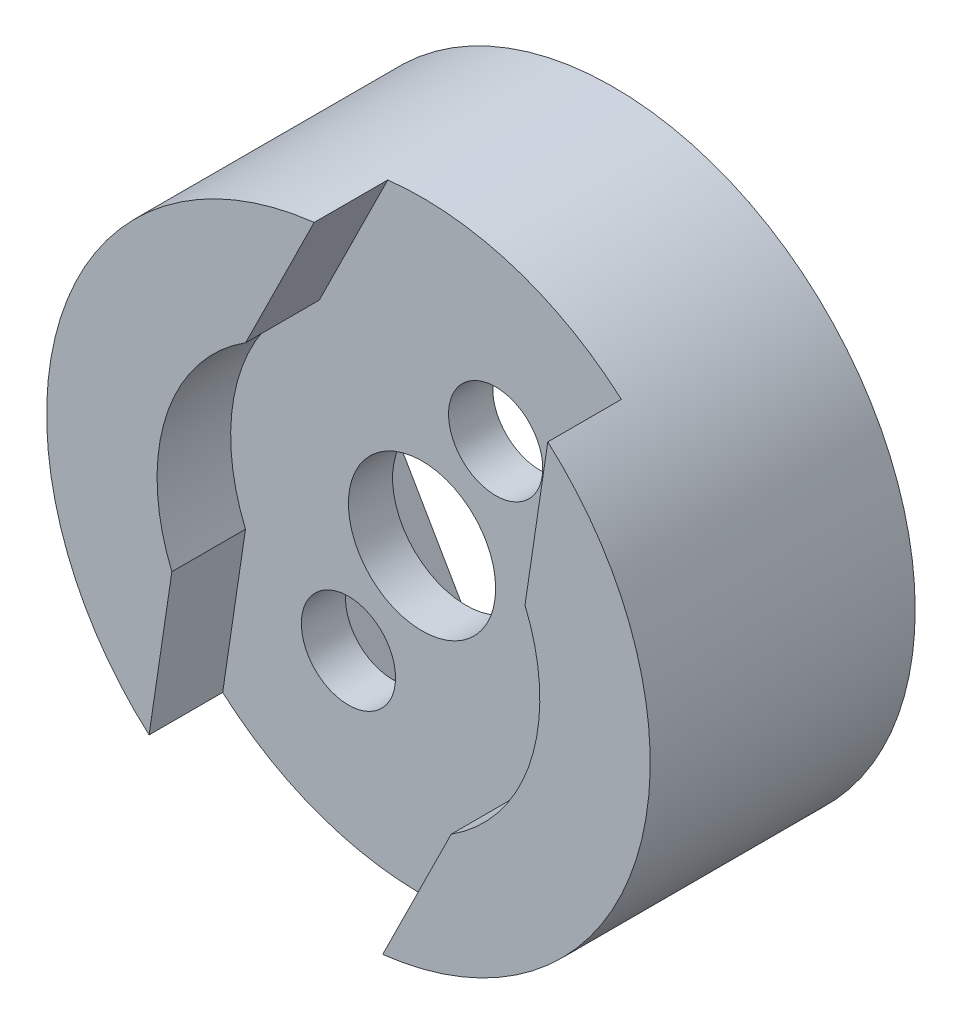
SolidWorks part; units mm, degrees
ref_plane "Front Plane" through (0, 0, 0) normal (0, 0, 1) x (1, 0, 0)
ref_plane "Top Plane" through (0, 0, 0) normal (0, 1, 0) x (1, 0, 0)
ref_plane "Right Plane" through (0, 0, 0) normal (1, 0, 0) x (0, 0, -1)
sketch "Sketch1" plane through (0, 0, 0) normal (0, 0, 1) x (1, 0, 0)
  line L1 (4.75, 8.2272) -> (-4.75, 8.2272)
  line L2 (-4.75, 8.2272) -> (-9.5, 0)
  line L3 (-9.5, 0) -> (-4.75, -8.2272)
  line L4 (-4.75, -8.2272) -> (4.75, -8.2272)
  line L5 (4.75, -8.2272) -> (9.5, 0)
  line L6 (9.5, 0) -> (4.75, 8.2272)
  circle A0 centre (0, 0) radius 10.25
  circle A1 centre (0, 0) radius 8.2272 construction
  dimension "D1" = 20.5
  dimension "D2" = 9.5
extrude "Boss-Extrude1" add sketch "Sketch1" along normal blind 5
sketch "Sketch2" plane through (0, 0, 5) normal (0, 0, 1) x (1, 0, 0)
  circle A1 centre (0, 0) radius 10.25
  circle A2 centre (0, 0) radius 10.25
  dimension "D1" = 0
extrude "Boss-Extrude2" add sketch "Sketch2" along normal blind 4
sketch "Sketch3" plane through (0, 0, 9) normal (0, 0, 1) x (1, 0, 0)
  line L0 (-5.9969, -2.5073) -> (-7.9048, -15.3014)
  line L1 (-2.2492, -17.0751) -> (3.491, -5.4829)
  line L2 (5.9969, 2.5073) -> (7.9048, 15.3014)
  line L3 (2.2492, 17.0751) -> (-3.491, 5.4829)
  line L5 (-2.2492, -17.0751) -> (3.5543, -5.3553) construction
  line L6 (5.9759, 2.3664) -> (7.9048, 15.3014) construction
  line L7 (2.2492, 17.0751) -> (-3.5543, 5.3553) construction
  line L8 (-5.4814, -2.4401) -> (-7.4103, -15.3752) construction
  line L9 (-2.6972, -16.8533) -> (3.1062, -5.1334) construction
  line L10 (5.4814, 2.4401) -> (7.4103, 15.3752)
  line L11 (2.6972, 16.8533) -> (-3.1062, 5.1334) construction
  line L12 (-5.9759, -2.3664) -> (-7.9048, -15.3014) construction
  arc A0 (3.1062, -5.1334) -> (5.4814, 2.4401) centre (0, 0) ccw
  arc A1 (-3.1062, 5.1334) -> (-5.4814, -2.4401) centre (0, 0) ccw construction
  arc A2 (-7.9048, -15.3014) -> (-2.2492, -17.0751) centre (-4.9376, -15.7439) ccw
  arc A3 (-3.491, 5.4829) -> (-5.9969, -2.5073) centre (0, 0) ccw
  arc A4 (7.9048, 15.3014) -> (2.2492, 17.0751) centre (4.9376, 15.7439) ccw
  circle A5 centre (0, 0) radius 10.25 construction
  arc A6 (3.491, -5.4829) -> (5.9969, 2.5073) centre (0, 0) ccw
  arc A8 (3.365, -5.5612) -> (5.9382, 2.6435) centre (0, 0) ccw construction
  arc A9 (-3.1062, 5.1334) -> (-5.4814, -2.4401) centre (0, 0) ccw construction
  arc A10 (-7.4103, -15.3752) -> (-2.6972, -16.8533) centre (-4.9376, -15.7439) ccw
  arc A11 (3.1062, -5.1334) -> (5.4814, 2.4401) centre (0, 0) ccw
  arc A12 (7.4103, 15.3752) -> (2.6972, 16.8533) centre (4.9376, 15.7439) ccw
  arc A13 (-3.365, 5.5612) -> (-5.9382, -2.6435) centre (0, 0) ccw construction
  dimension "D1" = 6
  dimension "D2" = 2.6972
  dimension "D3" = 6
  dimension "D4" = 2.5
  dimension "D5" = 6
  dimension "D6" = 2.5
  dimension "D21" = 0.5
  dimension "D7" = 3.1062
  dimension "D8" = 4.9376
  dimension "D9" = 5.4814
  dimension "D10" = 7.4103
  dimension "D11" = 2.6972
  dimension "D12" = 3.1062
  dimension "D13" = 4.9376
  dimension "D14" = 5.4814
  dimension "D15" = 7.4103
  dimension "D16" = 2.4401
  dimension "D17" = 5.1334
  dimension "D18" = 15.3752
  dimension "D19" = 15.3752
  dimension "D20" = 0.5
extrude "Cut-Extrude1" cut sketch "Sketch3" against normal blind 2.5 and the other way through all
sketch "Sketch4" plane through (0, 0, 5) normal (0, 0, -1) x (-1, 0, 0)
  line L0 (-4.75, 8.2272) -> (4.75, 8.2272) construction
  circle A0 centre (2.5, -4.3301) radius 1.6
  circle A1 centre (-2.5, 4.3301) radius 1.6
  dimension "D1" = 3.2
  dimension "D2" = 3.2
  dimension "D3" = 2.25
  dimension "D4" = 7.25
  dimension "D5" = 3.8971
  dimension "D6" = 12.5574
extrude "Cut-Extrude2" cut sketch "Sketch4" against normal through all both and the other way through all
sketch "Sketch5" plane through (0, 0, 5) normal (0, 0, -1) x (-1, 0, 0)
  line L0 (-4.75, 8.2272) -> (4.75, 8.2272) construction
  circle A0 centre (0, 0) radius 2.5
  dimension "D1" = 5
  dimension "D2" = 4.75
  dimension "D3" = 8.2272
extrude "Cut-Extrude3" cut sketch "Sketch5" against normal through all both and the other way through all
